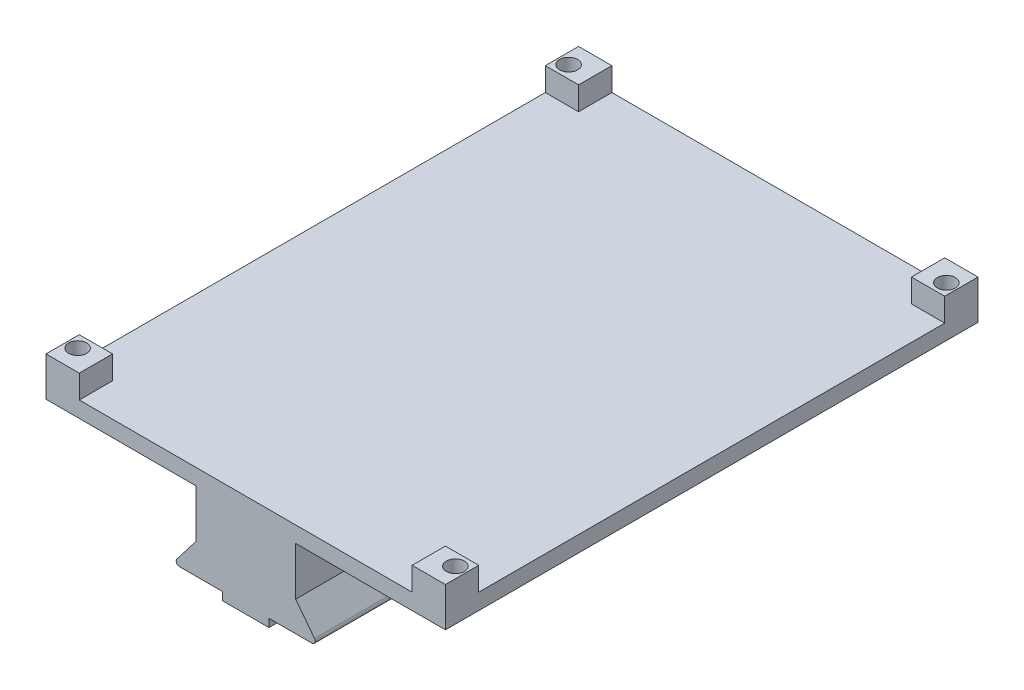
SolidWorks part; units mm, degrees
ref_plane "Front Plane" through (0, 0, 0) normal (0, 0, 1) x (1, 0, 0)
ref_plane "Top Plane" through (0, 0, 0) normal (0, 1, 0) x (1, 0, 0)
ref_plane "Right Plane" through (0, 0, 0) normal (1, 0, 0) x (0, 0, -1)
sketch "Sketch1" plane through (0, 0, 0) normal (0, 0, 1) x (1, 0, 0)
  line L0 (-9.525, 2.8575) -> (-9.525, 4.453)
  line L1 (-9.525, -2.8575) -> (-4.445, -2.8575)
  line L2 (9.525, 4.453) -> (9.525, 12.073)
  line L3 (4.445, -2.8575) -> (9.525, -2.8575)
  line L4 (9.525, 12.073) -> (38.1, 12.073)
  line L5 (-9.525, -2.8575) -> (9.525, 2.8575) construction
  line L6 (-9.525, 2.8575) -> (9.525, -2.8575) construction
  line L7 (0, -0.912) -> (0, 1.6828) construction
  line L8 (9.525, 2.8575) -> (9.525, 4.453)
  line L9 (0, 22.3477) -> (0, 5.1568) construction
  line L10 (-9.525, 2.8575) -> (-13.1264, -1.8359)
  line L11 (-9.525, -2.8575) -> (-12.6226, -2.8575)
  line L12 (-4.445, -2.8575) -> (-4.445, -4.3815)
  line L13 (4.445, -2.8575) -> (4.445, -4.3815)
  line L14 (-4.445, -4.3815) -> (4.445, -4.3815)
  line L15 (-38.1, 12.073) -> (-38.1, 19.5689)
  line L16 (-38.1, 19.5689) -> (-31.75, 19.5689)
  line L17 (9.525, -2.8575) -> (12.6226, -2.8575)
  line L18 (9.525, 2.8575) -> (13.1264, -1.8359)
  line L19 (-31.75, 19.5689) -> (-31.75, 15.1248)
  line L20 (-31.75, 15.1248) -> (31.75, 15.1248)
  line L21 (-9.525, 4.453) -> (-9.525, 12.073)
  line L22 (-9.525, 12.073) -> (-38.1, 12.073)
  line L23 (38.1, 12.073) -> (38.1, 19.5689)
  line L24 (38.1, 19.5689) -> (31.75, 19.5689)
  line L25 (31.75, 19.5689) -> (31.75, 15.1248)
  arc A0 (-13.1264, -1.8359) -> (-12.6226, -2.8575) centre (-12.6226, -2.2225) ccw
  arc A2 (13.1264, -1.8359) -> (12.6226, -2.8575) centre (12.6226, -2.2225) cw
  point P0 (0, 0)
  point P33 (0, 15.1248)
  point P35 (0, 15.1248)
  dimension "D1" = 5.715
  dimension "D2" = 19.05
  dimension "D3" = 1.5955
  dimension "D4" = 5.9159
  dimension "D5" = 3.0976
  dimension "D6" = 0.635
  dimension "D7" = 7.62
  dimension "D8" = 1.524
  dimension "D9" = 5.08
extrude "Boss-Extrude1" add sketch "Sketch1" along normal blind 101.6 contours L0 L21 L22 L15 L16 L19 L20 L25 L24 L23 L4 L2 L8 L18 A2 L17 L3 L13 L14 L12 L1 L11 A0 L10
sketch "Sketch4" plane through (0, 19.5689, 0) normal (0, 1, 0) x (1, 0, 0)
  line L0 (-38.1, -101.6) -> (-38.1, 0) construction
  line L1 (-38.1, -6.35) -> (-31.75, -6.35)
  line L2 (-38.1, -6.35) -> (-38.1, -95.25)
  line L3 (-38.1, -95.25) -> (-31.75, -95.25)
  line L4 (-31.75, -6.35) -> (-31.75, -95.25)
  line L5 (-31.75, -101.6) -> (-31.75, 0) construction
extrude "Cut-Extrude1" cut sketch "Sketch4" against normal up to surface (4.4441 mm away) up to face at (0, 15.1248, 50.8)
sketch "Sketch5" plane through (0, 19.5689, 0) normal (0, 1, 0) x (1, 0, 0)
  line L0 (31.75, -101.6) -> (31.75, 0) construction
  line L1 (31.75, -6.35) -> (38.1, -6.35)
  line L2 (31.75, -6.35) -> (31.75, -95.25)
  line L3 (31.75, -95.25) -> (38.1, -95.25)
  line L4 (38.1, -6.35) -> (38.1, -95.25)
  line L5 (38.1, -101.6) -> (38.1, 0) construction
extrude "Cut-Extrude2" cut sketch "Sketch5" against normal up to surface (4.4441 mm away) up to face at (-17.4625, 15.1248, 50.8)
sketch "Sketch6" plane through (0, 19.5689, 0) normal (0, 1, 0) x (1, 0, 0)
  line L0 (0, 101.6) -> (0, -101.6)
  line L1 (-114.3, -50.8) -> (38.1, -50.8)
  line L3 (38.1, -6.35) -> (38.1, -95.25) construction
  line L5 (-31.75, -101.6) -> (31.75, -101.6) construction
  point P0 (-36.0363, -3.9687)
  point P1 (36.0362, -3.9687)
  point P4 (36.0362, -97.6313)
  point P5 (0, 0)
  point P6 (0, 0)
  point P12 (-38.1, -50.8)
  point P13 (-36.0363, -97.6313)
  point P17 (-36.0363, -3.9687)
  dimension "D1" = 36.0363
hole_wizard "#4 Clearance Hole1" positions "3DSketch2" profile "Sketch8" hole size "#4" standard "ANSI Inch" end condition through all
sketch3d "3DSketch2"
  point P0 (-36.0363, 19.5689, 3.9687)
sketch "Sketch8" plane through (-36.0363, 19.5689, 3.9687) normal (1, 0, 0) x (0, 0, 1)
  line L0 (0, 0) -> (0, 23.9504)
  line L1 (0, 23.9504) -> (1.7272, 23.9504)
  line L2 (1.7272, 23.9504) -> (1.7272, 0)
  line L5 (1.7272, 0) -> (0, 0)
  line L11 (0, -6.35) -> (0, 107.95) construction
  dimension "Thru Hole Dia." = 3.4544
  dimension "Thru Hole Depth" = 23.9504
hole_wizard "#4 Clearance Hole2" positions "3DSketch3" profile "Sketch9" hole size "#4" standard "ANSI Inch" end condition through all
sketch3d "3DSketch3"
  point P0 (36.0362, 19.5689, 3.9687)
sketch "Sketch9" plane through (36.0362, 19.5689, 3.9687) normal (1, 0, 0) x (0, 0, 1)
  line L0 (0, 0) -> (0, 23.9504)
  line L1 (0, 23.9504) -> (1.7272, 23.9504)
  line L2 (1.7272, 23.9504) -> (1.7272, 0)
  line L5 (1.7272, 0) -> (0, 0)
  line L11 (0, -6.35) -> (0, 107.95) construction
  dimension "Thru Hole Dia." = 3.4544
  dimension "Thru Hole Depth" = 23.9504
hole_wizard "#4 Clearance Hole3" positions "3DSketch4" profile "Sketch10" hole size "#4" standard "ANSI Inch" end condition through all
sketch3d "3DSketch4"
  point P0 (-36.0363, 19.5689, 97.6313)
sketch "Sketch10" plane through (-36.0363, 19.5689, 97.6313) normal (1, 0, 0) x (0, 0, 1)
  line L0 (0, 0) -> (0, 23.9504)
  line L1 (0, 23.9504) -> (1.7272, 23.9504)
  line L2 (1.7272, 23.9504) -> (1.7272, 0)
  line L5 (1.7272, 0) -> (0, 0)
  line L11 (0, -6.35) -> (0, 107.95) construction
  dimension "Thru Hole Dia." = 3.4544
  dimension "Thru Hole Depth" = 23.9504
hole_wizard "#4 Clearance Hole4" positions "3DSketch5" profile "Sketch11" hole size "#4" standard "ANSI Inch" end condition through all
sketch3d "3DSketch5"
  point P0 (36.0362, 19.5689, 97.6313)
sketch "Sketch11" plane through (36.0362, 19.5689, 97.6313) normal (1, 0, 0) x (0, 0, 1)
  line L0 (0, 0) -> (0, 23.9504)
  line L1 (0, 23.9504) -> (1.7272, 23.9504)
  line L2 (1.7272, 23.9504) -> (1.7272, 0)
  line L5 (1.7272, 0) -> (0, 0)
  line L11 (0, -6.35) -> (0, 107.95) construction
  dimension "Thru Hole Dia." = 3.4544
  dimension "Thru Hole Depth" = 23.9504
